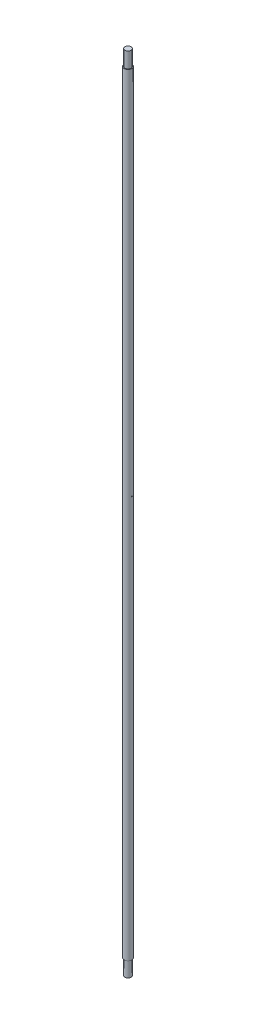
SolidWorks part; units mm, degrees
ref_plane "Plan de face" through (0, 0, 0) normal (0, 0, 1) x (1, 0, 0)
ref_plane "Plan de dessus" through (0, 0, 0) normal (0, 1, 0) x (1, 0, 0)
ref_plane "Plan de droite" through (0, 0, 0) normal (1, 0, 0) x (0, 0, -1)
sketch "Esquisse1" plane through (0, 0, 0) normal (0, 1, 0) x (1, 0, 0)
  circle A0 centre (0, 0) radius 5
extrude "Boss.-Extru.1" add sketch "Esquisse1" along normal blind 1000
sketch "Esquisse2" plane through (0, 1000, 0) normal (0, 1, 0) x (1, 0, 0)
  circle A0 centre (0, 0) radius 4
extrude "Boss.-Extru.2" add sketch "Esquisse2" along normal blind 20
sketch "Esquisse3" plane through (0, 0, 0) normal (0, -1, 0) x (-1, 0, 0)
  circle A0 centre (0, 0) radius 4
extrude "Boss.-Extru.3" add sketch "Esquisse3" along normal blind 20
hole_wizard "Dégagement M11" positions "Esquisse3D1" profile "Esquisse4" hole size "M1" standard "ISO" end condition through all
sketch3d "Esquisse3D1"
  point P0 (5, 520, 0)
sketch "Esquisse4" plane through (5, 520, 0) normal (0, 1, 0) x (0, 0, -1)
  line L0 (0, 0) -> (0, 10)
  line L1 (0, 10) -> (0.6, 10)
  line L2 (0.6, 10) -> (0.6, 0)
  line L5 (0.6, 0) -> (0, 0)
  line L11 (0, -6.35) -> (0, 107.95) construction
  dimension "Diamètre du perçage jusqu'au prochain" = 1.2
  dimension "Profondeur du perçage jusqu'au prochain" = 10
